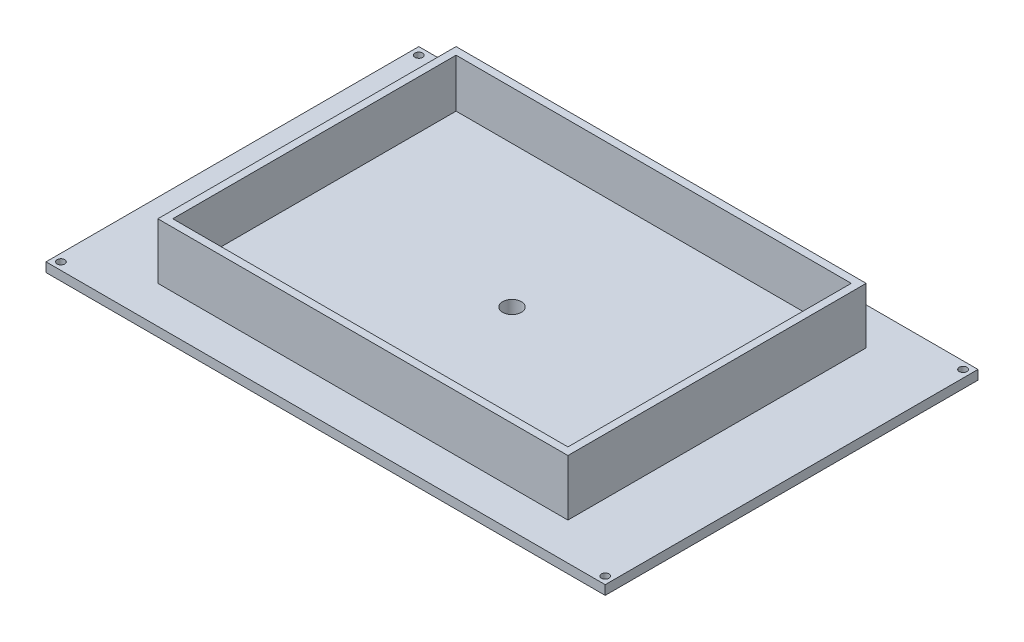
SolidWorks part; units mm, degrees
ref_plane "Front Plane" through (0, 0, 0) normal (0, 0, 1) x (1, 0, 0)
ref_plane "Top Plane" through (0, 0, 0) normal (0, 1, 0) x (1, 0, 0)
ref_plane "Right Plane" through (0, 0, 0) normal (1, 0, 0) x (0, 0, -1)
sketch "Sketch2" plane through (0, 0, 0) normal (0, 1, 0) x (1, 0, 0)
  line L1 (110, -80) -> (-110, -80)
  line L2 (110, -80) -> (110, 80)
  line L3 (110, 80) -> (-110, 80)
  line L4 (-110, -80) -> (-110, 80)
  line L5 (110, -80) -> (-110, 80) construction
  line L6 (110, 80) -> (-110, -80) construction
  line L7 (-86, -42.5) -> (-30, -42.5) construction
  line L8 (-86, -42.5) -> (-86, 42.5) construction
  line L9 (-86, 42.5) -> (-30, 42.5) construction
  line L10 (-30, -42.5) -> (-30, 42.5) construction
  line L11 (-86, -42.5) -> (-30, 42.5) construction
  line L12 (-86, 42.5) -> (-30, -42.5) construction
  line L13 (30, -59.5) -> (102, -59.5) construction
  line L14 (30, -59.5) -> (30, 59.5) construction
  line L15 (30, 59.5) -> (102, 59.5) construction
  line L16 (102, -59.5) -> (102, 59.5) construction
  line L17 (30, -59.5) -> (102, 59.5) construction
  line L18 (30, 59.5) -> (102, -59.5) construction
  circle A0 centre (0, 0) radius 10
  point P0 (0, 0)
  point P6 (-58, 0)
  point P11 (66, 0)
  dimension "D7" = 20
  dimension "D1" = 56
  dimension "D2" = 85
  dimension "D3" = 72
  dimension "D4" = 119
  dimension "D5" = 30
  dimension "D6" = 30
  dimension "D8" = 220
  dimension "D9" = 160
extrude "Boss-Extrude1" add sketch "Sketch2" along normal blind 30 contours L2 L1 L4 L3
sketch "Sketch3" plane through (0, 30, 0) normal (0, 1, 0) x (1, 0, 0)
  line L0 (110, 80) -> (-110, 80) construction
  line L1 (-106, -76) -> (106, -76)
  line L2 (-106, -76) -> (-106, 76)
  line L3 (-106, 76) -> (106, 76)
  line L4 (106, -76) -> (106, 76)
  line L5 (-106, -76) -> (106, 76) construction
  line L6 (-106, 76) -> (106, -76) construction
  line L7 (-110, 80) -> (-110, -80) construction
  point P0 (0, 0)
  dimension "D1" = 4
  dimension "D2" = 4
extrude "Cut-Extrude1" cut sketch "Sketch3" against normal blind 26
sketch "Sketch4" plane through (0, 0, 0) normal (0, -1, 0) x (1, 0, 0)
  line L1 (-150, -100) -> (150, -100)
  line L2 (-150, -100) -> (-150, 100)
  line L3 (-150, 100) -> (150, 100)
  line L4 (150, -100) -> (150, 100)
  line L5 (-150, -100) -> (150, 100) construction
  line L6 (-150, 100) -> (150, -100) construction
  point P0 (0, 0)
  dimension "D1" = 300
  dimension "D2" = 200
extrude "Boss-Extrude2" add sketch "Sketch4" along normal blind 5
sketch "Sketch5" plane through (0, -5, 0) normal (0, -1, 0) x (1, 0, 0)
  line L0 (-150, 100) -> (150, -100) construction
  line L1 (150, 100) -> (-150, 100) construction
  line L2 (-150, 100) -> (-150, -100) construction
  line L3 (0, 0) -> (0, 55.9052) construction
  line L4 (0, 0) -> (-37.3243, 0) construction
  circle A0 centre (-146, 96) radius 2.05
  circle A1 centre (146, 96) radius 2.05
  circle A2 centre (146, -96) radius 2.05
  circle A3 centre (-146, -96) radius 2.05
  dimension "D1" = 4.1
  dimension "D2" = 4
  dimension "D3" = 4
extrude "Cut-Extrude2" cut sketch "Sketch5" against normal up to next
sketch "Sketch6" plane through (0, 4, 0) normal (0, 1, 0) x (1, 0, 0)
  circle A0 centre (0, 0) radius 5
  dimension "D1" = 10
extrude "Cut-Extrude3" cut sketch "Sketch6" against normal through all
